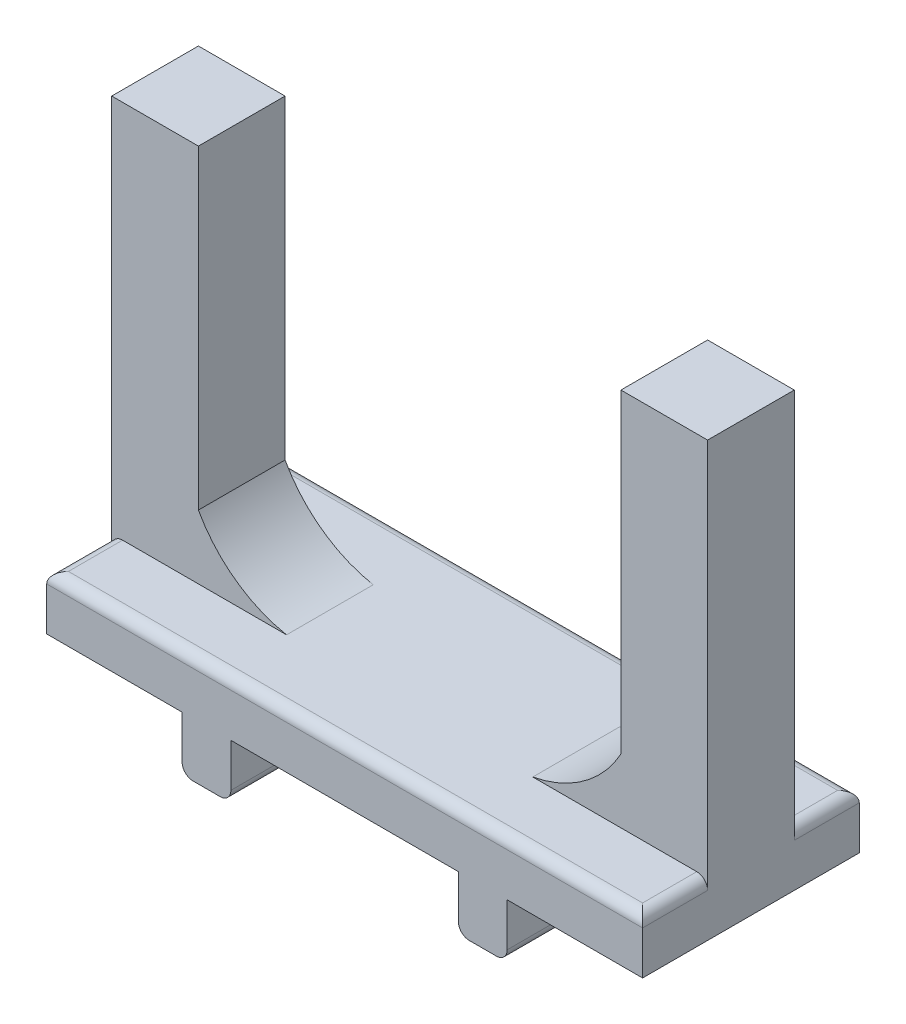
SolidWorks part; units mm, degrees
ref_plane "Front Plane" through (0, 0, 0) normal (0, 0, 1) x (1, 0, 0)
ref_plane "Top Plane" through (0, 0, 0) normal (0, 1, 0) x (1, 0, 0)
ref_plane "Right Plane" through (0, 0, 0) normal (1, 0, 0) x (0, 0, -1)
sketch "Sketch1" plane through (0, 0, 0) normal (0, 0, 1) x (1, 0, 0)
  line L0 (0, 0) -> (0, 35.9328) construction
  line L2 (-27.5, 2.5) -> (27.5, 2.5)
  line L3 (-27.5, 2.5) -> (-27.5, -2.5)
  line L4 (-27.5, -2.5) -> (27.5, -2.5)
  line L5 (27.5, 2.5) -> (27.5, -2.5)
  line L6 (-27.5, 2.5) -> (27.5, -2.5) construction
  line L7 (-27.5, -2.5) -> (27.5, 2.5) construction
  line L8 (-15, -2.5) -> (-10.5, -2.5)
  line L9 (-15, -2.5) -> (-15, -7.5)
  line L10 (-15, -7.5) -> (-10.5, -7.5)
  line L11 (-10.5, -2.5) -> (-10.5, -7.5)
  line L12 (10.5, -2.5) -> (15, -2.5)
  line L13 (10.5, -2.5) -> (10.5, -7.5)
  line L14 (10.5, -7.5) -> (15, -7.5)
  line L15 (15, -2.5) -> (15, -7.5)
  dimension "D1" = 5
  dimension "D2" = 55
  dimension "D3" = 5
  dimension "D4" = 4.5
  dimension "D5" = 5
  dimension "D6" = 4.5
  dimension "D7" = 21
  dimension "D8" = 10.5
extrude "Boss-Extrude2" add sketch "Sketch1" along normal blind 20 contours L5 L2 L3 L4 | L11 L4 L9 L10 | L15 L4 L13 L14
sketch "Sketch2" plane through (0, 2.5, 0) normal (0, 1, 0) x (1, 0, 0)
  line L0 (0, 0) -> (0, -20) construction
  line L1 (-27.5, 0) -> (27.5, 0) construction
  line L2 (-27.5, -20) -> (27.5, -20) construction
  line L3 (-27.5, -10) -> (27.5, -10) construction
  line L4 (-27.5, -20) -> (-27.5, 0) construction
  line L5 (27.5, -20) -> (27.5, 0) construction
  line L6 (27.5, -14) -> (19.5, -14)
  line L7 (-27.5, -6) -> (-19.5, -6)
  line L8 (-27.5, -6) -> (-27.5, -14)
  line L9 (-27.5, -14) -> (-19.5, -14)
  line L10 (-19.5, -6) -> (-19.5, -14)
  line L11 (-27.5, -6) -> (-19.5, -14) construction
  line L12 (-27.5, -14) -> (-19.5, -6) construction
  line L13 (19.5, -6) -> (19.5, -14)
  line L14 (27.5, -6) -> (19.5, -6)
  line L15 (27.5, -6) -> (27.5, -14)
  point P12 (-23.5, -10)
  dimension "D1" = 8
  dimension "D2" = 8
  dimension "D3" = 8
extrude "Boss-Extrude3" add sketch "Sketch2" along normal blind 35
fillet "Fillet1" radius 1 10 edges at (-10.5, -7.5, 10) (10.5, -7.5, 10) (15, -7.5, 10) (-15, -7.5, 10) (27.5, 2.5, 3) (27.5, 2.5, 17) (0, 2.5, 0) (0, 2.5, 20) (-27.5, 2.5, 3) (-27.5, 2.5, 17)
ref_plane "Plane1" through (0, 0, 10) normal (0, 0, 1) x (1, 0, 0)
sketch "Sketch9" plane through (0, 0, 10) normal (0, 0, 1) x (1, 0, 0)
  line L0 (-19.5, 8.4051) -> (-19.5, 2.5)
  line L1 (-19.5, 37.5) -> (-19.5, 2.5) construction
  line L2 (-26.5, 2.5) -> (-19.5, 2.5) construction
  line L3 (-19.5, 2.5) -> (-11.3641, 2.5)
  line L4 (-26.5, 2.5) -> (26.5, 2.5) construction
  arc A0 (-19.5, 8.4051) -> (-11.3641, 2.5) centre (-9.1583, 14.0965) ccw
extrude "Boss-Extrude4" add sketch "Sketch9" along normal blind 4 and the other way blind 4
mirror "Mirror1" about plane through (0, 0, 0) normal (1, 0, 0) of "Boss-Extrude4"
